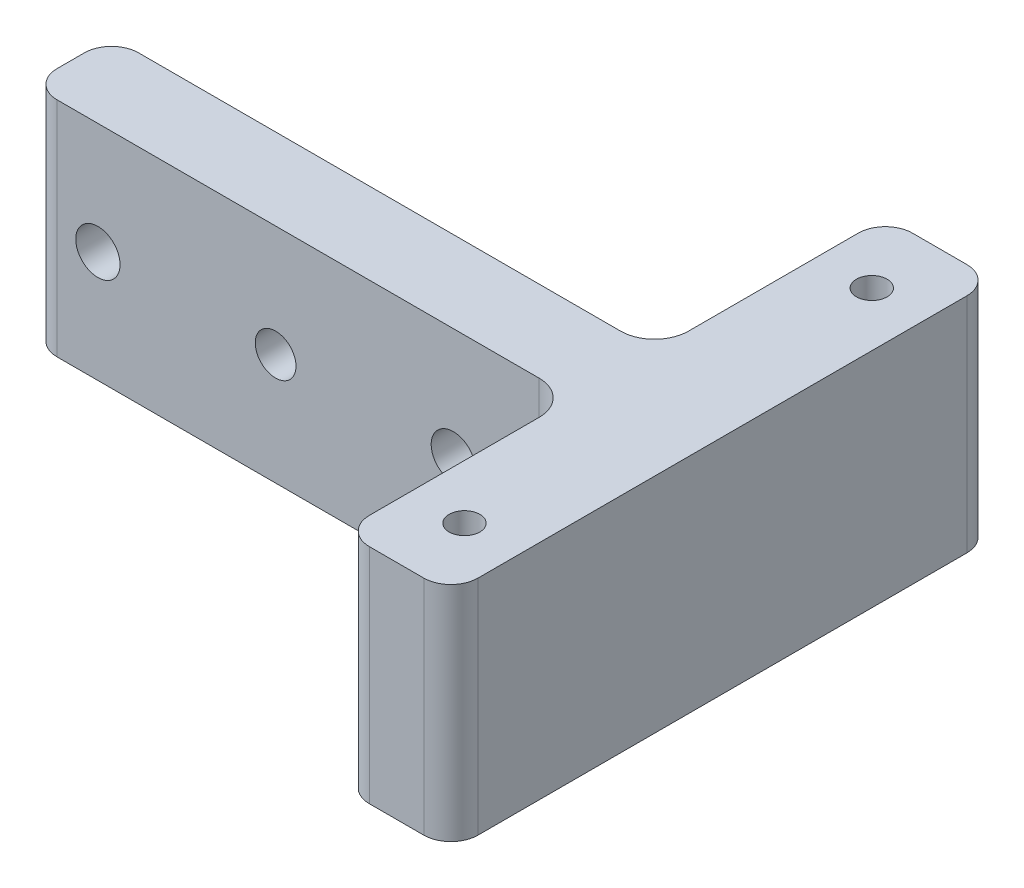
SolidWorks part; units mm, degrees
material "Delrin 2700 NC010, Low Viscosity Acetal Copolymer (SS)"
ref_plane "Front Plane" through (0, 0, 0) normal (0, 0, 1) x (1, 0, 0)
ref_plane "Top Plane" through (0, 0, 0) normal (0, 1, 0) x (1, 0, 0)
ref_plane "Right Plane" through (0, 0, 0) normal (1, 0, 0) x (0, 0, -1)
sketch "Sketch1" plane through (0, 0, 0) normal (0, 1, 0) x (1, 0, 0)
  line L0 (-4, -3) -> (-4, -20)
  line L1 (-4, 20) -> (4, 20)
  line L2 (-4, 20) -> (-4, 3)
  line L3 (-4, -20) -> (4, -20)
  line L4 (4, 20) -> (4, -20)
  line L5 (-4, 20) -> (4, -20) construction
  line L6 (-4, -20) -> (4, 20) construction
  line L7 (-4, -3) -> (-44, -3)
  line L9 (-4, 3) -> (-44, 3)
  line L10 (-44, -3) -> (-44, 3)
  point P0 (0, 0)
  point P10 (-44, 0)
  dimension "D1" = 8
  dimension "D2" = 40
  dimension "D3" = 40
  dimension "D4" = 6
extrude "Boss-Extrude1" add sketch "Sketch1" along normal blind 16.4
hole_wizard "#4-40 Tapped Hole1" positions "Sketch4" profile "Sketch5" tap size "#4-40" standard "ANSI Inch" end condition through all
sketch "Sketch4" plane through (0, 16.4, 0) normal (0, 1, 0) x (1, 0, 0)
  line L1 (-4, -20) -> (4, -20) construction
  line L2 (4, 20) -> (-4, 20) construction
  point P0 (0, 15)
  point P2 (0, -15)
  dimension "D1" = 5
  dimension "D2" = 5
sketch "Sketch5" plane through (0, 16.4, -15) normal (1, 0, 0) x (0, 0, 1)
  line L0 (0, 0) -> (0, 16.4)
  line L1 (0, 16.4) -> (1.1303, 16.4)
  line L2 (1.1303, 16.4) -> (1.1303, 0)
  line L5 (1.1303, 0) -> (0, 0)
  line L11 (0, -6.35) -> (0, 107.95) construction
  dimension "Thru Tap Drill Dia." = 2.2606
  dimension "Thru Tap Drill Depth" = 16.4
cosmetic thread "Hole Thread1" parameters "D2"=2.8448
cosmetic thread "Hole Thread2" parameters "D2"=2.8448
hole_wizard "Ø3.0mm Dowel Hole1" positions "Sketch6" profile "Sketch7" hole size "Ø3.0" standard "ANSI Metric" end condition through all
sketch "Sketch6" plane through (0, 0, 3) normal (0, 0, 1) x (1, 0, 0)
  line L0 (-44, 16.4) -> (-44, 0) construction
  line L1 (-44, 0) -> (-4, 0) construction
  point P0 (-25.91, 8.2)
  dimension "D1" = 18.09
  dimension "D2" = 8.2
sketch "Sketch7" plane through (-25.91, 8.2, 3) normal (1, 0, 0) x (0, -1, 0)
  line L0 (0, 0) -> (0, 23)
  line L1 (0, 23) -> (1.5, 23)
  line L2 (1.5, 23) -> (1.5, 0)
  line L5 (1.5, 0) -> (0, 0)
  line L11 (0, -6.35) -> (0, 107.95) construction
  dimension "Thru Hole Dia." = 3
  dimension "Thru Hole Depth" = 23
hole_wizard "#4 Clearance Hole1" positions "Sketch8" profile "Sketch9" hole size "#4" standard "ANSI Inch" end condition through all
sketch "Sketch8" plane through (0, 0, 3) normal (0, 0, 1) x (1, 0, 0)
  line L0 (-44, 16.4) -> (-44, 0) construction
  line L1 (-44, 0) -> (-4, 0) construction
  point P0 (-39, 8.2)
  point P2 (-12.82, 8.2)
  dimension "D1" = 5
  dimension "D2" = 26.18
  dimension "D3" = 8.2
sketch "Sketch9" plane through (-39, 8.2, 3) normal (1, 0, 0) x (0, -1, 0)
  line L0 (0, 0) -> (0, 23)
  line L1 (0, 23) -> (1.6319, 23)
  line L2 (1.6319, 23) -> (1.6319, 0)
  line L5 (1.6319, 0) -> (0, 0)
  line L11 (0, -6.35) -> (0, 107.95) construction
  dimension "Thru Hole Dia." = 3.2639
  dimension "Thru Hole Depth" = 23
fillet "Fillet1" radius 2.5 2 edges at (-4, 8.2, -3) (-4, 8.2, 3)
fillet "Fillet2" radius 2 6 edges at (-4, 8.2, -20) (4, 8.2, -20) (-4, 8.2, 20) (4, 8.2, 20) (-44, 8.2, 3) (-44, 8.2, -3)
equation "\"D2@Sketch4\"=\"D1@Sketch4\""
